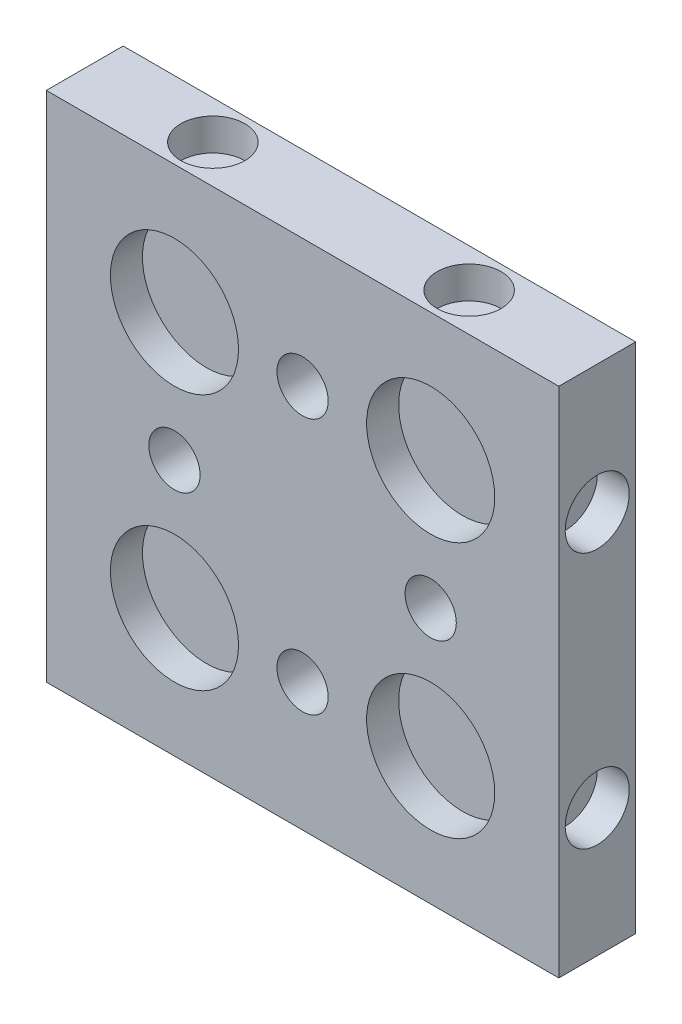
SolidWorks part; units mm, degrees
ref_plane "Front Plane" through (0, 0, 0) normal (0, 0, 1) x (1, 0, 0)
ref_plane "Top Plane" through (0, 0, 0) normal (0, 1, 0) x (1, 0, 0)
ref_plane "Right Plane" through (0, 0, 0) normal (1, 0, 0) x (0, 0, -1)
sketch "Sketch1" plane through (0, 0, 0) normal (0, 0, 1) x (1, 0, 0)
  line L1 (-21.3507, 25.9522) -> (29.4493, 25.9522)
  line L2 (-21.3507, 25.9522) -> (-21.3507, -24.8478)
  line L3 (-21.3507, -24.8478) -> (29.4493, -24.8478)
  line L4 (29.4493, 25.9522) -> (29.4493, -24.8478)
  dimension "D1" = 50.8
  dimension "D2" = 50.8
extrude "Boss-Extrude1" add sketch "Sketch1" along normal blind 7.62
sketch "Sketch2" plane through (0, 0, 7.62) normal (0, 0, 1) x (1, 0, 0)
  line L0 (4.0493, 25.9522) -> (4.0493, -24.8478)
  line L1 (29.4493, 25.9522) -> (-21.3507, 25.9522) construction
  line L2 (-21.3507, -24.8478) -> (29.4493, -24.8478) construction
  line L3 (29.4493, 0.5522) -> (-21.3507, 0.5522)
  line L4 (29.4493, -24.8478) -> (29.4493, 25.9522) construction
  line L5 (-21.3507, 25.9522) -> (-21.3507, -24.8478) construction
  line L6 (-8.6507, 25.9522) -> (-8.6507, -24.8478)
  line L7 (16.7493, 25.9522) -> (16.7493, -24.8478)
  line L8 (-21.3507, 13.2522) -> (29.4493, 13.2522)
  line L9 (29.4493, -12.1478) -> (-21.3507, -12.1478)
  dimension "D1" = 12.7
  dimension "D2" = 12.7
  dimension "D3" = 12.7
  dimension "D4" = 12.7
sketch "Sketch3" plane through (0, 0, 7.62) normal (0, 0, 1) x (1, 0, 0)
  line L0 (-8.6507, 25.9522) -> (-8.6507, -24.8478) construction
  line L1 (-21.3507, 13.2522) -> (29.4493, 13.2522) construction
  line L2 (29.4493, -12.1478) -> (-21.3507, -12.1478) construction
  line L3 (16.7493, 25.9522) -> (16.7493, -24.8478) construction
  circle A0 centre (-8.6507, 0.5522) radius 2.54
  circle A1 centre (4.0493, 13.2522) radius 2.54
  circle A2 centre (4.0493, -12.1478) radius 2.54
  circle A3 centre (16.7493, 0.5522) radius 2.54
extrude "Cut-Extrude1" cut sketch "Sketch3" against normal blind 6.35
sketch "Sketch4" plane through (0, 0, 7.62) normal (0, 0, 1) x (1, 0, 0)
  line L0 (-8.6507, 25.9522) -> (-8.6507, -24.8478) construction
  line L1 (-21.3507, 13.2522) -> (29.4493, 13.2522) construction
  line L3 (29.4493, -24.8478) -> (29.4493, 25.9522) construction
  line L4 (29.4493, 25.9522) -> (-21.3507, 25.9522) construction
  line L5 (-21.3507, -24.8478) -> (29.4493, -24.8478) construction
  circle A0 centre (-8.6507, 13.2522) radius 6.35
  circle A2 centre (16.7493, 13.2522) radius 6.35
  circle A3 centre (16.7493, -12.1478) radius 6.35
  circle A4 centre (-8.6507, -12.1478) radius 6.35
  dimension "D1" = 12.7
  dimension "D5" = 12.7
  dimension "D3" = 12.7
  dimension "D4" = 12.7
extrude "Cut-Extrude2" cut sketch "Sketch4" against normal blind 3.175
sketch "Sketch5" plane through (29.4493, 0, 0) normal (1, 0, 0) x (0, 0, -1)
  line L0 (-7.62, 25.9522) -> (0, 25.9522) construction
  line L1 (-7.62, -24.8478) -> (-7.62, 25.9522) construction
  line L2 (-7.62, -24.8478) -> (0, -24.8478) construction
  circle A0 centre (-3.81, 13.2522) radius 3.175
  circle A1 centre (-3.81, -12.1478) radius 3.175
  dimension "D1" = 3.81
  dimension "D2" = 12.7
  dimension "D3" = 3.81
  dimension "D4" = 12.7
extrude "Cut-Extrude3" cut sketch "Sketch5" against normal blind 3.175
sketch "Sketch6" plane through (0, -24.8478, 0) normal (0, -1, 0) x (-1, 0, 0)
  line L0 (21.3507, -7.62) -> (21.3507, 0) construction
  line L1 (21.3507, -7.62) -> (-29.4493, -7.62) construction
  line L2 (-29.4493, -7.62) -> (-29.4493, 0) construction
  circle A0 centre (8.6507, -3.81) radius 3.175
  circle A1 centre (-16.7493, -3.81) radius 3.175
  dimension "D1" = 12.7
  dimension "D3" = 3.81
  dimension "D2" = 3.81
  dimension "D4" = 12.7
extrude "Cut-Extrude4" cut sketch "Sketch6" against normal blind 3.175
sketch "Sketch7" plane through (-21.3507, 0, 0) normal (-1, 0, 0) x (0, 0, 1)
  line L0 (7.62, 25.9522) -> (0, 25.9522) construction
  line L1 (7.62, 25.9522) -> (7.62, -24.8478) construction
  line L2 (7.62, -24.8478) -> (0, -24.8478) construction
  line L3 (7.62, 25.9522) -> (7.62, -24.8478) construction
  circle A0 centre (3.81, 13.2522) radius 3.175
  circle A1 centre (3.81, -12.1478) radius 3.175
  dimension "D1" = 12.7
  dimension "D3" = 12.7
  dimension "D2" = 3.81
  dimension "D4" = 3.81
extrude "Cut-Extrude5" cut sketch "Sketch7" against normal blind 3.175
sketch "Sketch8" plane through (0, 25.9522, 0) normal (0, 1, 0) x (1, 0, 0)
  line L0 (-21.3507, -7.62) -> (-21.3507, 0) construction
  line L1 (29.4493, -7.62) -> (-21.3507, -7.62) construction
  line L2 (29.4493, -7.62) -> (29.4493, 0) construction
  line L3 (29.4493, -7.62) -> (-21.3507, -7.62) construction
  circle A0 centre (-8.6507, -3.81) radius 3.175
  circle A1 centre (16.7493, -3.81) radius 3.175
  dimension "D3" = 12.7
  dimension "D4" = 3.81
  dimension "D1" = 12.7
  dimension "D2" = 3.81
extrude "Cut-Extrude6" cut sketch "Sketch8" against normal blind 3.175
